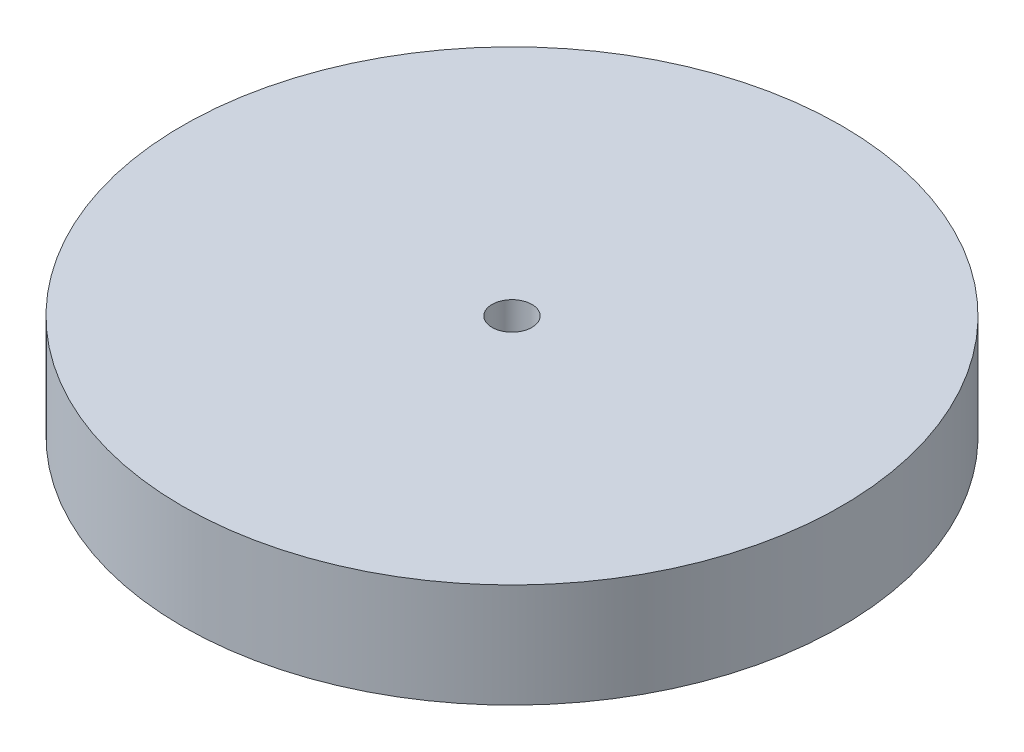
SolidWorks part; units mm, degrees
ref_plane "Front Plane" through (0, 0, 0) normal (0, 0, 1) x (1, 0, 0)
ref_plane "Top Plane" through (0, 0, 0) normal (0, 1, 0) x (1, 0, 0)
ref_plane "Right Plane" through (0, 0, 0) normal (1, 0, 0) x (0, 0, -1)
sketch "Sketch1" plane through (0, 0, 0) normal (0, 1, 0) x (1, 0, 0)
  circle A0 centre (0, 0) radius 19
  circle A1 centre (0, 0) radius 1.15
  dimension "D1" = 38
  dimension "D2" = 2.3
extrude "Boss-Extrude1" add sketch "Sketch1" against normal blind 6
